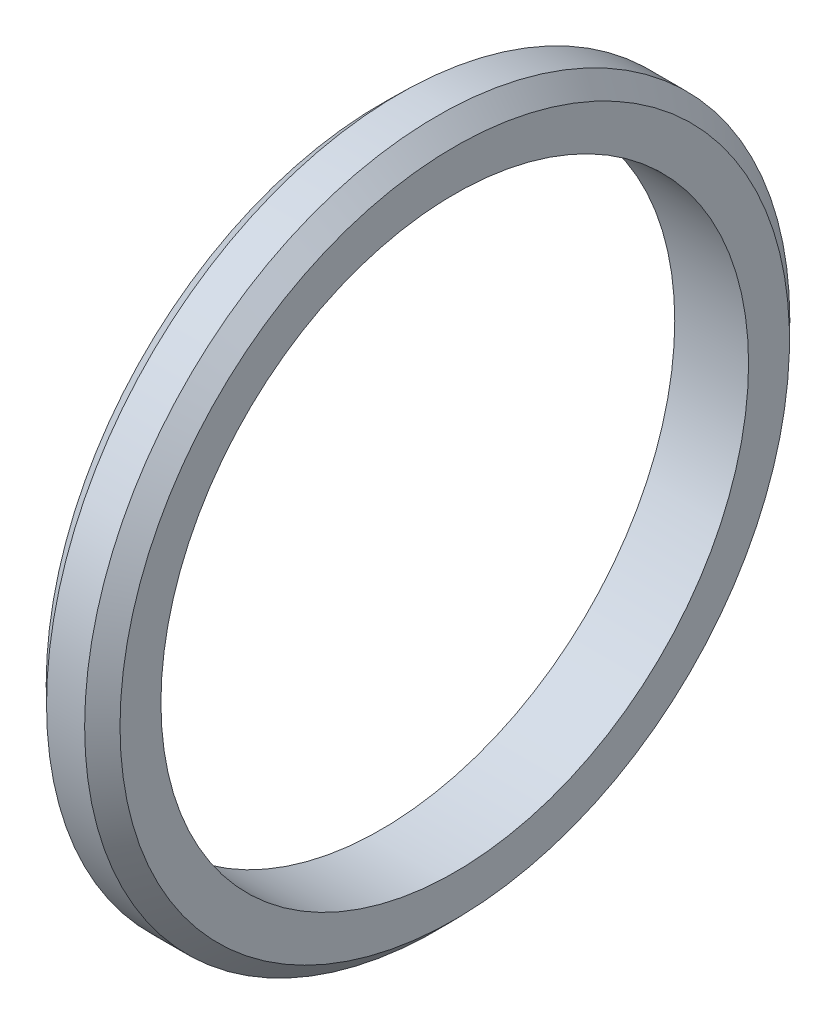
SolidWorks part; units mm, degrees
ref_plane "Front Plane" through (0, 0, 0) normal (0, 0, 1) x (1, 0, 0)
ref_plane "Top Plane" through (0, 0, 0) normal (0, 1, 0) x (1, 0, 0)
ref_plane "Right Plane" through (0, 0, 0) normal (1, 0, 0) x (0, 0, -1)
sketch "Sketch3" plane through (0, 0, 0) normal (0, 1, 0) x (1, 0, 0)
  line L0 (0, 0) -> (0, 15.875) construction
  line L1 (-1.9939, 15.875) -> (1.9939, 15.875)
  line L2 (1.9939, 15.875) -> (1.9939, 18.0859)
  line L3 (1.9939, 18.0859) -> (1.0469, 19.05)
  line L4 (1.0469, 19.05) -> (-1.0124, 19.05)
  line L5 (-1.0124, 19.05) -> (-1.9939, 18.0859)
  line L6 (-1.9939, 18.0859) -> (-1.9939, 15.875)
  line L7 (0, 15.875) -> (0.0172, 19.05) construction
  line L8 (0, 0) -> (3.2422, 0) construction
  dimension "D1" = 15.875
  dimension "D2" = 3.175
  dimension "D3" = 3.9878
revolve "Revolve1" add sketch "Sketch3" angle 360 about L8
equation "\"D1@Sketch3\"=1.25/2"
